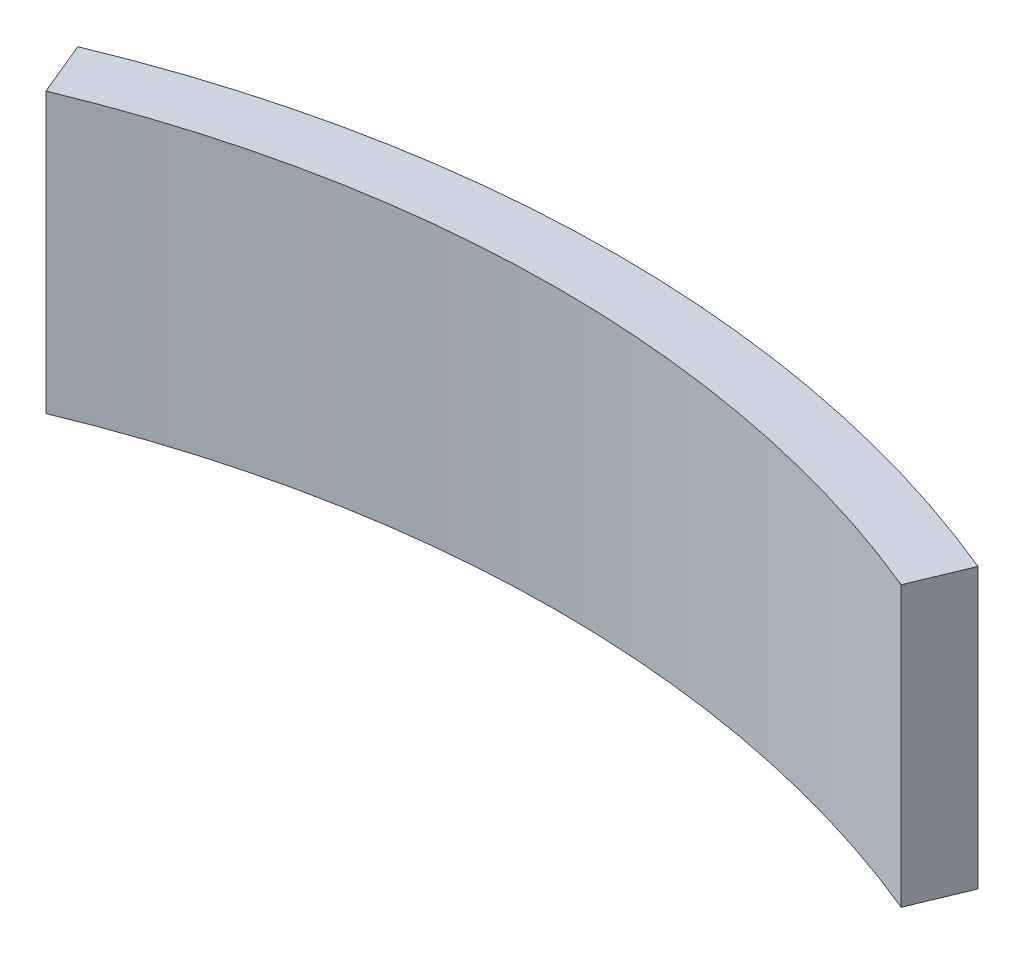
SolidWorks part; units mm, degrees
ref_plane "Front Plane" through (0, 0, 0) normal (0, 0, 1) x (1, 0, 0)
ref_plane "Top Plane" through (0, 0, 0) normal (0, 1, 0) x (1, 0, 0)
ref_plane "Right Plane" through (0, 0, 0) normal (1, 0, 0) x (0, 0, -1)
sketch "Sketch1" plane through (0, 0, 0) normal (0, 1, 0) x (1, 0, 0)
  line L0 (0, 0) -> (0, 117.7068) construction
  line L1 (0, 0) -> (-38.8326, 93.7503) construction
  line L2 (-30.6147, 73.9104) -> (-29.0839, 70.2148)
  line L3 (30.6147, 73.9104) -> (29.0839, 70.2148)
  arc A0 (30.6147, 73.9104) -> (-30.6147, 73.9104) centre (0, 0) ccw
  arc A1 (29.0839, 70.2148) -> (-29.0839, 70.2148) centre (0, 0) ccw
  arc A2 (-30.6147, 73.9104) -> (30.6147, 73.9104) centre (0, 0) ccw construction
  circle A3 centre (0, 0) radius 80 construction
  arc A4 (-29.0839, 70.2148) -> (29.0839, 70.2148) centre (0, 0) ccw construction
  circle A5 centre (0, 0) radius 76 construction
  dimension "D1" = 160
  dimension "D3" = 22.5
  dimension "D2" = 4
extrude "Boss-Extrude1" add sketch "Sketch1" along normal mid plane 19
